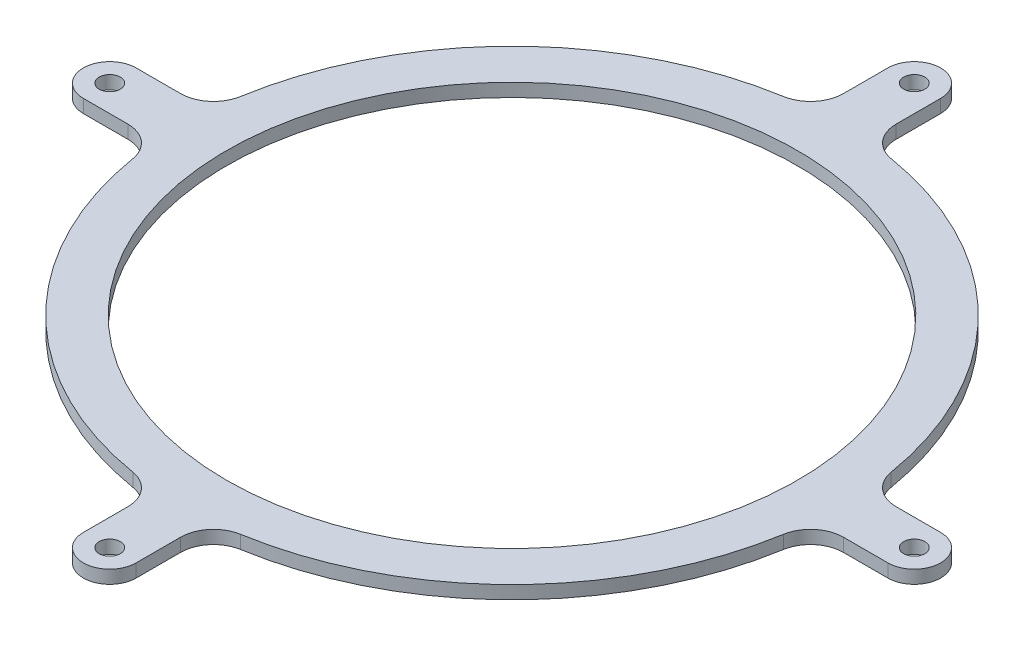
SolidWorks part; units mm, degrees
material "Thornel Mat VMA"
ref_plane "前视基准面" through (0, 0, 0) normal (0, 0, 1) x (1, 0, 0)
ref_plane "上视基准面" through (0, 0, 0) normal (0, 1, 0) x (1, 0, 0)
ref_plane "右视基准面" through (0, 0, 0) normal (1, 0, 0) x (0, 0, -1)
sketch "草图1" plane through (0, 0, 0) normal (0, 1, 0) x (1, 0, 0)
  circle A0 centre (0, 0) radius 43.3
  circle A1 centre (0, 0) radius 50
  dimension "D1" = 86.6
  dimension "D2" = 100
extrude "凸台-拉伸1" add sketch "草图1" along normal blind 2
sketch "草图2" plane through (0, 2, 0) normal (0, 1, 0) x (1, 0, 0)
  line L0 (-68.6608, 0) -> (79.6691, 0) construction
  line L1 (0, 69.5048) -> (0, -66.2856) construction
  line L2 (47.6834, 4) -> (47.6834, -4)
  line L3 (47.6834, 4) -> (61, 4)
  line L5 (61, -4) -> (47.6834, -4)
  line L6 (-4, -61) -> (-4, -47.6834)
  line L7 (4, -47.6834) -> (-4, -47.6834)
  line L8 (4, -47.6834) -> (4, -61)
  line L9 (-61, 4) -> (-47.6834, 4)
  line L10 (-47.6834, -4) -> (-47.6834, 4)
  line L11 (-47.6834, -4) -> (-61, -4)
  line L12 (4, 61) -> (4, 47.6834)
  line L13 (-4, 47.6834) -> (4, 47.6834)
  line L14 (-4, 47.6834) -> (-4, 61)
  arc A0 (61, 4) -> (61, -4) centre (61, 0) cw
  circle A1 centre (61, 0) radius 1.6
  circle A2 centre (0, -61) radius 1.6
  arc A3 (4, -61) -> (-4, -61) centre (0, -61) cw
  circle A4 centre (-61, 0) radius 1.6
  arc A5 (-61, -4) -> (-61, 4) centre (-61, 0) cw
  circle A6 centre (0, 61) radius 1.6
  arc A7 (-4, 61) -> (4, 61) centre (0, 61) cw
  point P8 (47.6834, 0)
  point P12 (0, 0)
  dimension "D3" = 3.2
  dimension "D1" = 8
  dimension "D2" = 61
  dimension "D4" = 4
extrude "凸台-拉伸2" add sketch "草图2" against normal blind 2
fillet "圆角1" radius 5 8 edges at (4, 1, 49.8397) (49.8397, 1, 4) (49.8397, 1, -4) (4, 1, -49.8397) (-4, 1, -49.8397) (-49.8397, 1, -4) (-49.8397, 1, 4) (-4, 1, 49.8397)
